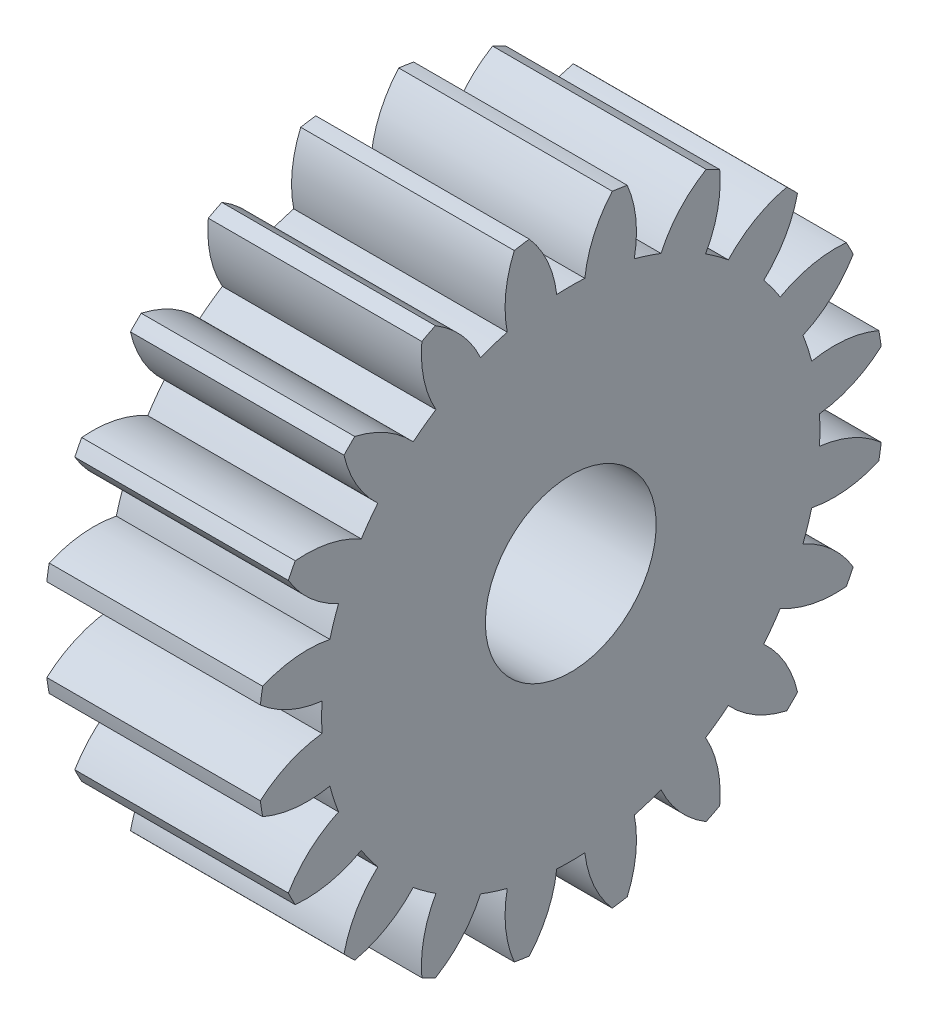
SolidWorks part; units mm, degrees
material "AISI 1045 Steel, cold drawn"
ref_plane "Plane1" through (0, 0, 0) normal (0, 0, 1) x (1, 0, 0)
ref_plane "Plane2" through (0, 0, 0) normal (0, 1, 0) x (1, 0, 0)
ref_plane "Plane3" through (0, 0, 0) normal (1, 0, 0) x (0, 0, -1)
sketch "HoldingSke" plane through (0, 0, 0) normal (0, 1, 0) x (1, 0, 0)
  line L0 (0, 0) -> (0.4698, -0.171)
  line L1 (-15, 0) -> (100, 0) construction
  line L2 (0, 0) -> (-2.1039, 2.3779)
  line L3 (0, 0) -> (-11.863, 4.5341)
  line L4 (0, 0) -> (8.1152, 2.9537)
  line L5 (0, 0) -> (-46.8476, -17.4728)
  line L6 (0, 0) -> (-12.4344, -8.3896)
  line L7 (-2.1039, 2.3779) -> (8.6586, 51.2059)
  line L8 (-76.2, 54.61) -> (-73.9, 54.61)
  line L9 (-71.009, 38.7566) -> (-53.1078, 45.2721)
  line L10 (-76.2, 71.12) -> (104.1128, 71.12)
  line L11 (0, 0) -> (-15, 0)
  line L12 (-76.2, 101.6) -> (-76.133, 101.6)
  line L13 (24.9733, 27.94) -> (52.9518, 28.4284)
  line L14 (24.9733, 27.94) -> (24.9743, 27.94)
  line L15 (24.9733, 27.94) -> (100.4006, 29.5858)
  line L16 (-63.627, -2) -> (-12.827, -2)
  circle A0 centre (0, 0) radius 6
  circle A1 centre (0, 0) radius 17.499
  circle A2 centre (0, 0) radius 37.5
  circle A3 centre (0, 0) radius 6
  dimension "MHD" = 34.998
  dimension "Hub_dia" = 75
  dimension "Bore" = 12
  dimension "MBD" = 12
  dimension "Num_teeth" = 20
  dimension "Pitch" = 0.5
  dimension "Overall_len" = 50
  dimension "Show_teeth" = 20
  dimension "Thickness" = 15
  dimension "OAL" = 50.0001
  dimension "T_dim" = 2.3
  dimension "Ap" = 20
  dimension "H" = 19.05
  dimension "Pitch_radius" = 180.3128
  dimension "Width" = 15
  dimension "Backlash" = 0.067
  dimension "Addendum_fac" = 1
  dimension "Dedendum_fac" = 1.25
  dimension "Clearance_fac" = 0.25
  dimension "Dedendum_add" = 0.001
  dimension "Module" = 2
sketch "BasProSke" plane through (0, 0, 0) normal (0, 1, 0) x (1, 0, 0)
  line L0 (-10, 0) -> (60, 0) construction
  line L1 (0, 0) -> (0, 22)
  line L2 (0, 0) -> (15, 0)
  line L3 (15, 0) -> (15, 22)
  line L4 (15, 22) -> (0, 22)
  dimension "Thickness" = 15
  dimension "Diameter" = 44
revolve "Base-Revolve" add sketch "BasProSke" angle 360 about L0
sketch "TooCutSke" plane through (0, 0, 0) normal (1, 0, 0) x (0, 0, -1)
  line L1 (0, 0) -> (0, 107) construction
  line L2 (0, 0) -> (-1.6864, 19.9288) construction
  line L3 (0, 0) -> (-6.2409, 39.4033) construction
  line L4 (-1.6864, 19.9288) -> (-3.1204, 19.7016) construction
  arc A0 (0.9862, 17.4712) -> (-0.9862, 17.4712) centre (0, 0) ccw
  arc A1 (2.9329, 21.8293) -> (-2.9329, 21.8293) centre (0, 0) ccw
  circle A2 centre (0, 0) radius 20 construction
  circle A3 centre (0, 0) radius 18.7939 construction
  arc A4 (-0.9862, 17.4712) -> (-2.9329, 21.8293) centre (-8.9313, 16.536) ccw
  arc A5 (2.9329, 21.8293) -> (0.9862, 17.4712) centre (8.9313, 16.536) ccw
  dimension "Root_dia" = 34.998
  dimension "Overcut_dia" = 44.0508
  dimension "Pitch_dia" = 40
  dimension "Base_dia" = 37.5877
  dimension "Flank_rad" = 8
  dimension "Half_ang" = 9
  dimension "Half_CT" = 1.4519
extrude "ToothCut" cut sketch "TooCutSke" along normal through all
fillet "Breaks" [suppressed] radius 0.04
fillet "RootFillets" [suppressed] radius 0.501
pattern_circular "TeethCuts" count 20 every 18 about axis through (-10, 0, 0) along (1, 0, 0) of "ToothCut", "RootFillets", "Breaks"
sketch "HubNeaOneSke" plane through (0, 0, 0) normal (-1, 0, 0) x (0, 0, 1)
  circle A0 centre (0, 0) radius 17.499
  dimension "Diameter" = 34.998
extrude "HubNearOne" [suppressed] add sketch "HubNeaOneSke" along normal blind 35.0001
sketch "HubNeaBotSke" plane through (0, 0, 0) normal (-1, 0, 0) x (0, 0, 1)
  circle A0 centre (0, 0) radius 17.499
  dimension "Diameter" = 34.998
extrude "HubNearBoth" [suppressed] add sketch "HubNeaBotSke" along normal blind 17.5
ref_plane "FarPln" through (15, 0, 0) normal (1, 0, 0) x (0, 0, -1)
sketch "HubFarSke" plane through (15, 0, 0) normal (1, 0, 0) x (0, 0, -1)
  circle A0 centre (0, 0) radius 17.499
  dimension "Diameter" = 34.998
extrude "HubFar" [suppressed] add sketch "HubFarSke" along normal blind 17.5
sketch "BorSke" plane through (0, 0, 0) normal (1, 0, 0) x (0, 0, -1)
  circle A0 centre (0, 0) radius 6
  dimension "Diameter" = 12
extrude "Bore" cut sketch "BorSke" along normal mid plane 100.0001
sketch "KeySke" plane through (0, 0, 0) normal (1, 0, 0) x (0, 0, -1)
  line L0 (-2, 0) -> (-2, 8.3)
  line L1 (-2, 8.3) -> (2, 8.3)
  line L2 (2, 8.3) -> (2, 0)
  line L3 (0, 0) -> (0, 34) construction
  line L4 (-2, 0) -> (2, 0)
  dimension "Offset" = 8.3
  dimension "Width" = 4
extrude "Keyway" [suppressed] cut sketch "KeySke" along normal mid plane 100.0001
pattern_circular "Keyway2" [suppressed] count 2 every 90 about axis through (-10, 0, 0) along (1, 0, 0)
equation "' \"Module@HoldingSke\" = 6.35"
equation "' \"Num_teeth@HoldingSke\" = 12"
equation "' \"Ap@HoldingSke\" =  20"
equation "' \"Ap@HoldingSke\" = 20"
equation "' \"Width@HoldingSke\" = 0.5 * 25.4"
equation "' \"Hub_dia@HoldingSke\"= 1 * 25.4"
equation "' \"Hub_dia@HoldingSke\" = 1 * 25.4"
equation "' \"Overall_len@HoldingSke\" = 1.0 * 25.4"
equation "' \"Bore@HoldingSke\" = 0.75 * 25.4"
equation "' \"T_dim@HoldingSke\" = 0.1 * 25.4"
equation "' \"Width@KeySke\" = 0.25 * 25.4"
equation "' \"Show_teeth@HoldingSke\" = 13"
equation "' \"Backlash@HoldingSke\" = 0.009 * 25.4"
equation "' \"Addendum_fac@HoldingSke\" = 1.0"
equation "' \"Dedendum_fac@HoldingSke\" = 1.25"
equation "' \"Dedendum_add@HoldingSke\" = 0.00005 * 25.4"
equation "' \"Clearance_fac@HoldingSke\" = 0.25"
equation "\"Pitch@HoldingSke\" = 1 / \"Module@HoldingSke\""
equation "\"Overcut_dia@TooCutSke\" = (\"Num_teeth@HoldingSke\" + 2 * \"Addendum_fac@HoldingSke\") / \"Pitch@HoldingSke\" + 0.002 * 25.4"
equation "\"Pitch_dia@TooCutSke\" = \"Num_teeth@HoldingSke\" / \"Pitch@HoldingSke\""
equation "\"Base_dia@TooCutSke\" = \"Num_teeth@HoldingSke\" / \"Pitch@HoldingSke\" * cos((\"Ap@HoldingSke\"  * 3.14159265 / 180))"
equation "\"Root_dia@TooCutSke\" = (\"Num_teeth@HoldingSke\" + 2) / \"Pitch@HoldingSke\" - 2 * (\"Addendum_fac@HoldingSke\" + \"Dedendum_fac@HoldingSke\") / \"Pitch@HoldingSke\" - \"Dedendum_add@HoldingSke\" * 2"
equation "\"Half_ang@TooCutSke\" = 180 / \"Num_teeth@HoldingSke\""
equation "\"Half_CT@TooCutSke\" = \"Num_teeth@HoldingSke\" / \"Pitch@HoldingSke\" * sin((3.14159265 / 2 / \"Num_teeth@HoldingSke\")) / 2 - 7 * \"Backlash@HoldingSke\" / 4"
equation "\"Flank_rad@TooCutSke\" = \"Num_teeth@HoldingSke\" / \"Pitch@HoldingSke\" / 5"
equation "\"Radius@RootFillets\" = \"Clearance_fac@HoldingSke\" / \"Pitch@HoldingSke\" + \"Dedendum_add@HoldingSke\""
equation "\"Break_rad@Breaks\" = 0.02 / \"Pitch@HoldingSke\""
equation "\"Thickness@HoldingSke\" = \"Width@HoldingSke\""
equation "\"OAL@HoldingSke\" = \"Thickness@HoldingSke\""
equation "\"MHD@HoldingSke\" = (\"Num_teeth@HoldingSke\" + 2) / \"Pitch@HoldingSke\" - 2 * (\"Addendum_fac@HoldingSke\" + \"Dedendum_fac@HoldingSke\")  / \"Pitch@HoldingSke\" - \"Dedendum_add@HoldingSke\" * 2"
equation "\"MBD@HoldingSke\" = (\"Num_teeth@HoldingSke\" + 2) / \"Pitch@HoldingSke\" - 2 * (\"Addendum_fac@HoldingSke\" + \"Dedendum_fac@HoldingSke\")  / \"Pitch@HoldingSke\" - \"Dedendum_add@HoldingSke\" * 2 - 0.002 * 25.4"
equation "\"MHD@HoldingSke\" = ((sgn( \"MHD@HoldingSke\" - \"Hub_dia@HoldingSke\" )-1)*( \"MHD@HoldingSke\" - \"Hub_dia@HoldingSke\" ))/-2+ \"Hub_dia@HoldingSke\""
equation "\"MBD@HoldingSke\" = ((sgn( \"MBD@HoldingSke\" - \"Bore@HoldingSke\" )-1)*( \"MBD@HoldingSke\" - \"Bore@HoldingSke\" ))/-2+ \"Bore@HoldingSke\""
equation "\"OAL@HoldingSke\" = ((sgn( \"OAL@HoldingSke\" - \"Overall_len@HoldingSke\" )+1)*( \"OAL@HoldingSke\" - \"Overall_len@HoldingSke\" ))/2 + \"Overall_len@HoldingSke\" + 0.000002 * 25.4"
equation "\"Num_teeth@TeethCuts\" = int( \"Show_teeth@HoldingSke\" ) + 1"
equation "\"Num_teeth@TeethCuts\" = ((sgn( \"Num_teeth@TeethCuts\" - \"Num_teeth@HoldingSke\" )-1)*( \"Num_teeth@TeethCuts\" - \"Num_teeth@HoldingSke\" ))/-2+ \"Num_teeth@HoldingSke\""
equation "\"Num_teeth@TeethCuts\" = ((sgn( \"Num_teeth@TeethCuts\" - 2.0)+1)*( \"Num_teeth@TeethCuts\" - 2.0))/2 +2.0"
equation "\"Angle@TeethCuts\" = 360.0 / \"Num_teeth@HoldingSke\""
equation "\"Diameter@BasProSke\" = (\"Num_teeth@HoldingSke\" + 2 * \"Addendum_fac@HoldingSke\") / \"Pitch@HoldingSke\""
equation "\"Thickness@BasProSke\"  = \"Thickness@HoldingSke\""
equation "' \"Fillet_rad@BasProSke\" =  \"Thickness@HoldingSke\" * 0.05"
equation "' \"Fillet_rad@BasProSke\" = \"Thickness@HoldingSke\" * 0.05"
equation "\"MHD@HoldingSke\" = ((sgn( \"MHD@HoldingSke\" - \"Root_dia@TooCutSke\" )-1)*( \"MHD@HoldingSke\" - \"Root_dia@TooCutSke\" ))/-2+ \"Root_dia@TooCutSke\""
equation "\"Diameter@HubNeaOneSke\" = \"MHD@HoldingSke\""
equation "\"Length@HubNearOne\" = \"OAL@HoldingSke\" - \"Thickness@BasProSke\""
equation "\"Diameter@HubNeaBotSke\" = \"MHD@HoldingSke\""
equation "\"Length@HubNearBoth\" = ( \"OAL@HoldingSke\" - \"Thickness@BasProSke\" ) / 2.0"
equation "\"Thickness@FarPln\" = \"Thickness@BasProSke\""
equation "\"Diameter@HubFarSke\" = \"MHD@HoldingSke\""
equation "\"Length@HubFar\" = ( \"OAL@HoldingSke\" - \"Thickness@BasProSke\" ) / 2.0"
equation "\"Diameter@BorSke\" = \"MBD@HoldingSke\""
equation "\"D1@Bore\" = \"OAL@HoldingSke\" * 2.0"
equation "\"D1@Keyway\" = \"OAL@HoldingSke\" * 2.0"
equation "\"Offset@KeySke\" = \"T_dim@HoldingSke\" + \"MBD@HoldingSke\" / 2.0"
